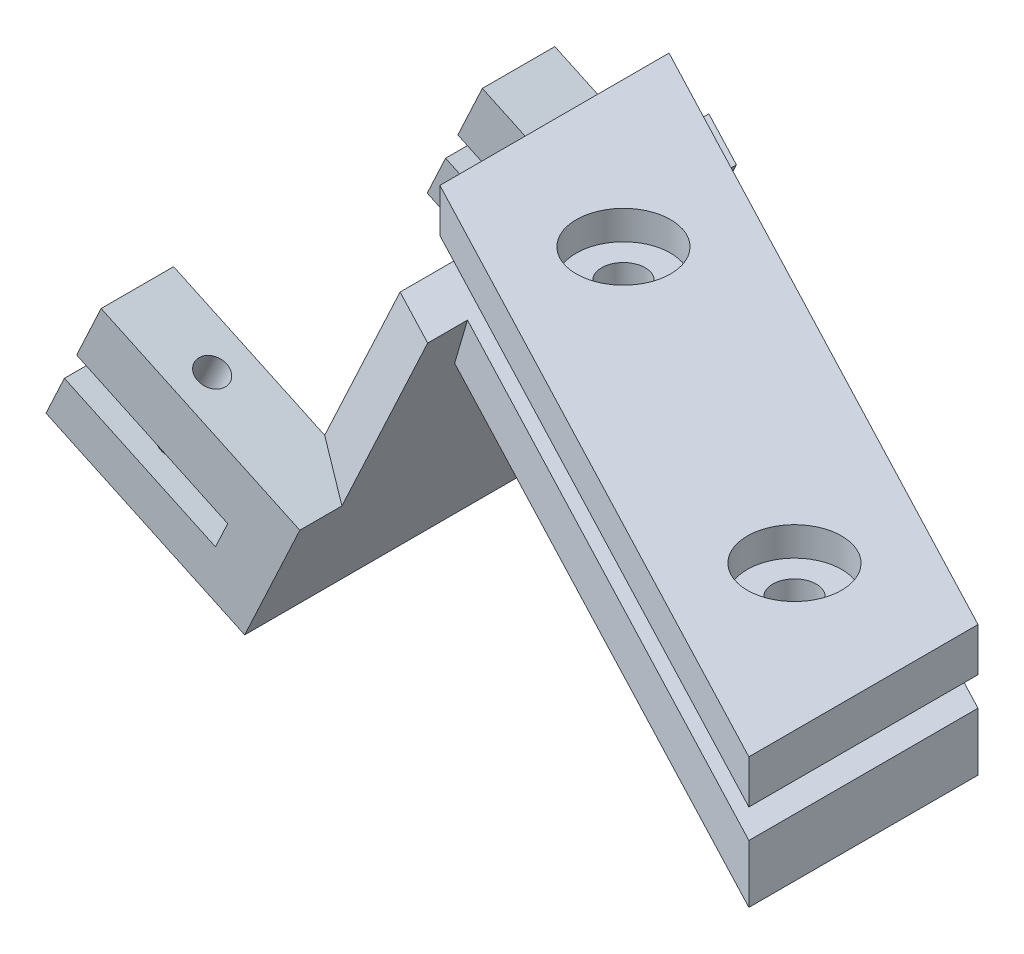
SolidWorks part; units mm, degrees
ref_plane "Front Plane" through (0, 0, 0) normal (0, 0, 1) x (1, 0, 0)
ref_plane "Top Plane" through (0, 0, 0) normal (0, 1, 0) x (1, 0, 0)
ref_plane "Right Plane" through (0, 0, 0) normal (1, 0, 0) x (0, 0, -1)
sketch "Sketch1" plane through (0, 0, 0) normal (0, 1, 0) x (1, 0, 0)
  line L0 (0, 6) -> (0, -19) construction
  line L1 (0, -19) -> (24.7992, -19) construction
  circle A0 centre (0, 0) radius 6
  circle A1 centre (24.7992, -13) radius 6
  dimension "D1" = 28
  dimension "D2" = 12
  dimension "D3" = 12
  dimension "D4" = 25
sketch "Sketch3" plane through (0, 0, 0) normal (0, 1, 0) x (1, 0, 0)
  line L0 (-10, 13.1456) -> (-10, -2.6614)
  line L1 (-10, -2.6614) -> (34.7992, -26.1456)
  line L2 (34.7992, -26.1456) -> (34.7992, -10.3386)
  line L3 (34.7992, -10.3386) -> (-10, 13.1456)
  line L5 (0, 0) -> (24.7992, -13) construction
  line L6 (0, 6) -> (0, -19) construction
  dimension "D1" = 7
  dimension "D2" = 7
  dimension "D3" = 10
  dimension "D4" = 10
extrude "Boss-Extrude1" add sketch "Sketch3" along normal blind 3
extrude "Boss-Extrude3" add sketch "Sketch1" against normal blind 2
sketch "Sketch4" plane through (0, 3, 0) normal (0, 1, 0) x (1, 0, 0)
  circle A0 centre (0, 0) radius 1.5
  circle A1 centre (24.7992, -13) radius 1.5
  dimension "D1" = 3
  dimension "D2" = 3
extrude "Cut-Extrude1" cut sketch "Sketch4" against normal through all
sketch "Sketch5" plane through (0, 3, 0) normal (0, 1, 0) x (1, 0, 0)
  circle A0 centre (0, 0) radius 3.25
  circle A1 centre (24.7992, -13) radius 3.25
  dimension "D1" = 6.5
  dimension "D2" = 6.5
extrude "Cut-Extrude2" cut sketch "Sketch5" against normal blind 2
sketch "Sketch6" plane through (0, -2, 0) normal (0, -1, 0) x (1, 0, 0)
  line L0 (-10, 2.6614) -> (-10, -13.1456)
  line L1 (-10, -13.1456) -> (34.7992, 10.3386)
  line L2 (34.7992, 10.3386) -> (34.7992, 26.1456)
  line L3 (34.7992, 26.1456) -> (-10, 2.6614)
  circle A0 centre (0, 0) radius 1.5
  circle A1 centre (24.7992, 13) radius 1.5
  circle A2 centre (24.7992, 13) radius 1.5 construction
  circle A3 centre (0, 0) radius 1.5 construction
extrude "Boss-Extrude4" add sketch "Sketch6" along normal blind 4 separate body
sketch "Sketch12" plane through (0, 0, 0) normal (0, 0, 1) x (1, 0, 0)
  line L0 (-10, -2) -> (-10, -18.3135)
  line L1 (-10, -18.3135) -> (-17.6071, -18.3135)
  line L2 (-17.6071, -18.3135) -> (-10, -2)
  line L3 (-10, -2) -> (-1.422, -6)
  line L4 (34.7992, -6) -> (-10, -6) construction
  dimension "D1" = 25
  dimension "D2" = 18
ref_plane "Plane1" through (0, -18.3135, 0) normal (0, -1, 0) x (-1, 0, 0)
sketch "Sketch7" plane through (0, -2, 0) normal (0, 1, 0) x (1, 0, 0)
  line L2 (-8, 14.8437) -> (-8, 12.0972) construction
  line L4 (-8, 12.0972) -> (-8, -3.7098) construction
  line L6 (-10, 15.8921) -> (-10, -5.4079)
  line L7 (-10, -5.4079) -> (-6, -7.5047)
  line L8 (-6, -7.5047) -> (-6, 13.7953)
  line L9 (-6, 13.7953) -> (-10, 15.8921)
  line L10 (-10, 13.1456) -> (34.7992, -10.3386) construction
  line L11 (-10, -2.6614) -> (-10, 13.1456) construction
  line L12 (34.7992, -26.1456) -> (-10, -2.6614) construction
  line L13 (-8, -3.7098) -> (-8, -6.4563) construction
  dimension "D1" = 21.3
  dimension "D2" = 4
sketch "Sketch16" plane through (0, -18.3135, 0) normal (0, -1, 0) x (-1, 0, 0)
  line L0 (13.6071, -7.5047) -> (13.6071, 13.7953)
  line L1 (13.6071, 13.7953) -> (17.6071, 15.8921)
  line L2 (17.6071, 15.8921) -> (17.6071, -5.4079)
  line L3 (17.6071, -5.4079) -> (13.6071, -7.5047)
  line L4 (6, 13.7953) -> (10, 15.8921) construction
  line L5 (10, 15.8921) -> (10, -5.4079) construction
  line L6 (10, -5.4079) -> (6, -7.5047) construction
loft "Loft1" add profiles "Sketch16", "Sketch7"
sketch "Sketch17" plane through (0, 0, 0) normal (0, 0, 1) x (1, 0, 0)
  line L0 (-17.6071, -18.3135) -> (-13.6071, -18.3135)
  line L1 (-13.6071, -18.3135) -> (-16.8927, -16.7815)
  line L2 (-17.6071, -18.3135) -> (-10, -2) construction
  line L3 (-16.8927, -16.7815) -> (-17.6071, -18.3135)
extrude "Cut-Extrude3" cut sketch "Sketch17" against normal through all both and the other way through all
sketch "Sketch9" plane through (-26.7054, -12.2057, 0) normal (0.4226, 0.9063, 0) x (-0.9063, 0.4226, 0)
  line L0 (-14.4524, 5.4079) -> (0.6729, 5.4079)
  line L2 (0.6729, 5.4079) -> (0.6729, 10.4079)
  line L3 (0.6729, 10.4079) -> (-14.4524, 10.4079)
  line L4 (-14.4524, 10.4079) -> (-14.4524, 5.4079)
  line L5 (-10.8271, -15.8921) -> (0.6729, -15.8921)
  line L6 (0.6729, -15.8921) -> (0.6729, -20.8921)
  line L7 (0.6729, -20.8921) -> (-14.4524, -20.8921)
  line L8 (-14.4524, -20.8921) -> (-14.4524, -15.8921)
  line L9 (-14.4524, -13.7953) -> (-10.8271, -15.8921)
  line L10 (-14.4524, -15.8921) -> (-14.4524, -13.7953)
  line L12 (-5.0771, 8.9579) -> (-5.0771, 10.4079) construction
  line L13 (-5.0771, -19.4421) -> (-5.0771, -20.8921) construction
  line L14 (-5.0771, 7.9579) -> (-5.0771, -18.4421) construction
  line L15 (-5.0771, -5.2421) -> (-10.8271, -5.2421) construction
  line L16 (-10.8271, -15.8921) -> (-10.8271, 5.4079) construction
  circle A0 centre (-5.0771, 7.9579) radius 1
  circle A1 centre (-5.0771, -18.4421) radius 1
  point P24 (-5.0771, -15.8921)
  dimension "D3" = 2
  dimension "D4" = 26.4
  dimension "D1" = 5
  dimension "D2" = 11.5
extrude "Boss-Extrude6" add sketch "Sketch9" along normal blind 4
sketch "Sketch10" plane through (-50.1145, -1.2899, 0) normal (0.4226, 0.9063, 0) x (-0.9063, 0.4226, 0)
  line L0 (-36.6562, 10.4079) -> (-36.6562, -20.8921)
  line L1 (-36.6562, -20.8921) -> (-40.2814, -20.8921)
  line L2 (-25.1562, -20.8921) -> (-40.2814, -20.8921) construction
  line L3 (-40.2814, -20.8921) -> (-40.2814, 10.4079)
  line L4 (-40.2814, 10.4079) -> (-25.1562, 10.4079) construction
  line L5 (-40.2814, 10.4079) -> (-36.6562, 10.4079)
  line L8 (-25.1562, 10.4079) -> (-40.2814, 10.4079) construction
  line L9 (-36.6562, -15.8921) -> (-36.6562, 5.4079) construction
extrude "Boss-Extrude7" add sketch "Sketch10" against normal blind 2
sketch "Sketch11" plane through (-10.29, -22.0671, 0) normal (-0.4226, -0.9063, 0) x (0.9063, -0.4226, 0)
  line L0 (-19.7178, 10.4079) -> (-4.5926, 10.4079)
  line L2 (-4.5926, 10.4079) -> (-4.5926, -20.8921)
  line L3 (-4.5926, -20.8921) -> (-19.7178, -20.8921)
  line L4 (-19.7178, -20.8921) -> (-19.7178, -15.8921)
  line L5 (-19.7178, -15.8921) -> (-8.2178, -15.8921)
  line L6 (-8.2178, -15.8921) -> (-8.2178, 5.4079)
  line L7 (-8.2178, 5.4079) -> (-19.7178, 5.4079)
  line L8 (-19.7178, 5.4079) -> (-19.7178, 10.4079)
  line L10 (-8.2178, -20.8921) -> (-8.2178, 10.4079) construction
  line L11 (-8.2178, -20.8921) -> (-8.2178, -15.8921) construction
  line L12 (-19.7178, -20.8921) -> (-19.7178, -15.8921) construction
  circle A0 centre (-13.9678, -18.4421) radius 1
  circle A1 centre (-13.9678, 7.9579) radius 1
  circle A2 centre (-13.9678, 7.9579) radius 1 construction
  circle A3 centre (-13.9678, -18.4421) radius 1 construction
extrude "Boss-Extrude8" add sketch "Sketch11" along normal blind 3
chamfer "Chamfer2" [suppressed] distance 4 angle 45
chamfer "Chamfer3" [suppressed] distance 2 angle 45
chamfer "Chamfer4" [suppressed] distance 20 distance2 4
